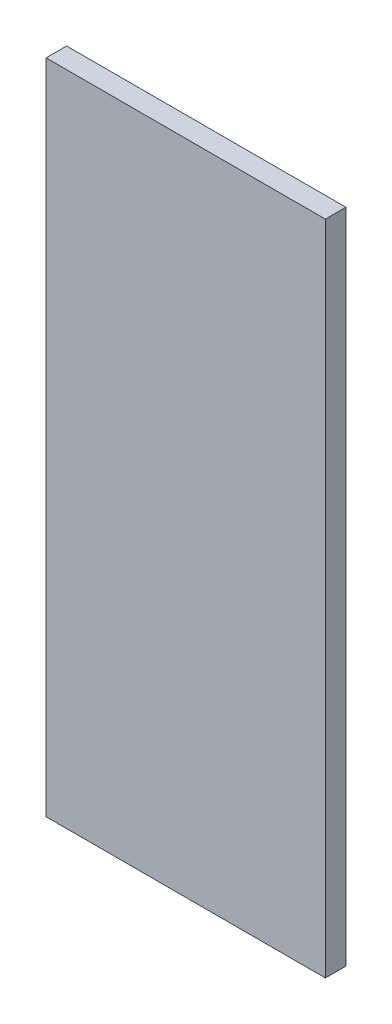
SolidWorks part; units mm, degrees
material "AISI 4340 Steel, normalized"
ref_plane "Front Plane" through (0, 0, 0) normal (0, 0, 1) x (1, 0, 0)
ref_plane "Top Plane" through (0, 0, 0) normal (0, 1, 0) x (1, 0, 0)
ref_plane "Right Plane" through (0, 0, 0) normal (1, 0, 0) x (0, 0, -1)
sketch "Sketch1" plane through (0, 0, 0) normal (0, 0, 1) x (1, 0, 0)
  line L1 (-10.795, 25.4) -> (10.795, 25.4)
  line L2 (-10.795, 25.4) -> (-10.795, -25.4)
  line L3 (-10.795, -25.4) -> (10.795, -25.4)
  line L4 (10.795, 25.4) -> (10.795, -25.4)
  line L5 (-10.795, 25.4) -> (10.795, -25.4) construction
  line L6 (-10.795, -25.4) -> (10.795, 25.4) construction
  point P0 (0, 0)
  dimension "D1" = 50.8
  dimension "D2" = 21.59
extrude "Boss-Extrude1" add sketch "Sketch1" along normal blind 1.5875
